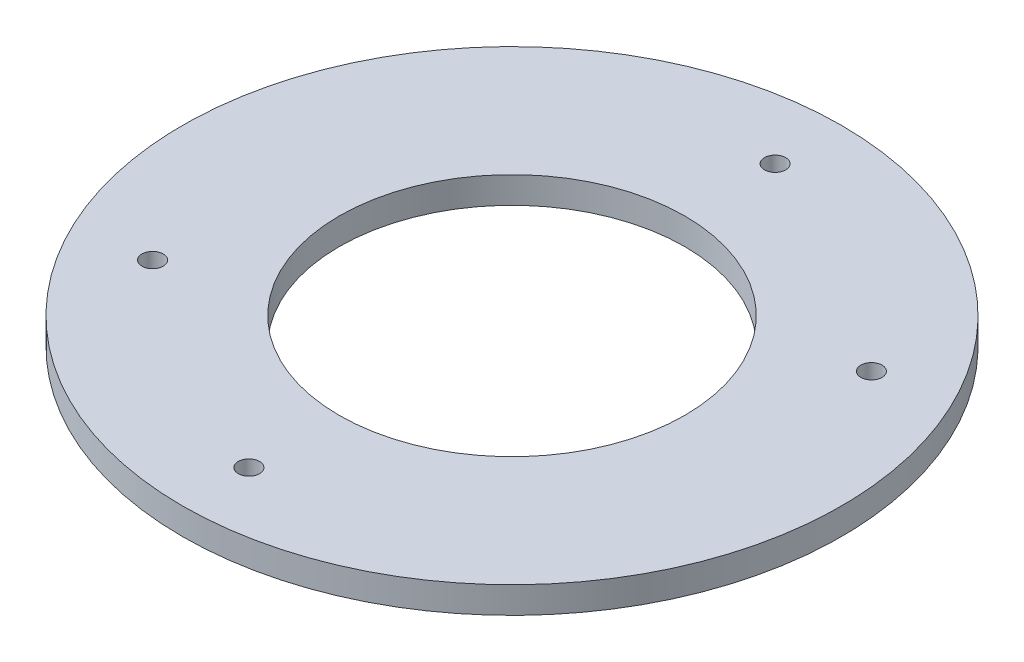
SolidWorks part; units mm, degrees
material "Polyetheretherketone (PEEK)"
ref_plane "Front Plane" through (0, 0, 0) normal (0, 0, 1) x (1, 0, 0)
ref_plane "Top Plane" through (0, 0, 0) normal (0, 1, 0) x (1, 0, 0)
ref_plane "Right Plane" through (0, 0, 0) normal (1, 0, 0) x (0, 0, -1)
sketch "Sketch1" plane through (0, 0, 0) normal (0, 1, 0) x (1, 0, 0)
  circle A0 centre (0, 0) radius 62
  dimension "D1" = 124
extrude "Boss-Extrude1" add sketch "Sketch1" along normal blind 5
sketch "Sketch2" plane through (0, 5, 0) normal (0, 1, 0) x (1, 0, 0)
  circle A0 centre (0, 49.5) radius 2
  dimension "D2" = 4
  dimension "D1" = 49.5
extrude "Cut-Extrude1" cut sketch "Sketch2" against normal blind 5 contours A0
pattern_circular "CirPattern1" count 2 every 120 about axis through (0, 5, 0) along (0, 1, 0) of "Cut-Extrude1"
sketch "Sketch4" plane through (0, 5, 0) normal (0, 1, 0) x (1, 0, 0)
  line L0 (0, 49.5) -> (-42.8683, -24.75) construction
  line L1 (0, 0) -> (-23.6703, -40.9981) construction
ref_plane "Plane1" through (0, 0, 0) normal (-0.866, 0, -0.5) x (-0.5, 0, 0.866)
mirror "Mirror1" about plane through (0, 0, 0) normal (-0.866, 0, -0.5) of "Cut-Extrude1", "CirPattern1"
sketch "Sketch5" plane through (0, 0, 0) normal (0, -1, 0) x (1, 0, 0)
  circle A0 centre (0, 0) radius 32.5
  dimension "D1" = 65
extrude "Cut-Extrude2" cut sketch "Sketch5" against normal blind 10
